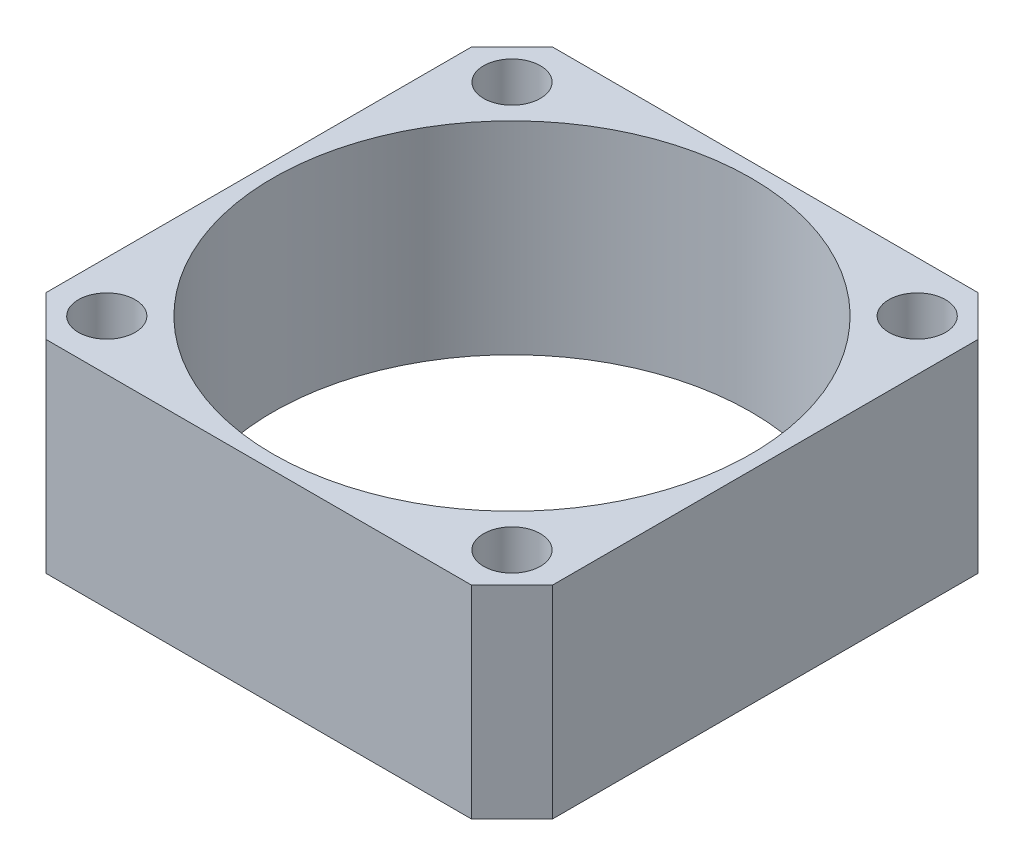
SolidWorks part; units mm, degrees
material "PET"
ref_plane "Front Plane" through (0, 0, 0) normal (0, 0, 1) x (1, 0, 0)
ref_plane "Top Plane" through (0, 0, 0) normal (0, 1, 0) x (1, 0, 0)
ref_plane "Right Plane" through (0, 0, 0) normal (1, 0, 0) x (0, 0, -1)
sketch "Sketch1" plane through (0, 0, 0) normal (0, 1, 0) x (1, 0, 0)
  line L0 (-12.5, 10.5) -> (-10.5, 12.5)
  line L1 (-10.5, -12.5) -> (10.5, -12.5)
  line L2 (-12.5, -10.5) -> (-12.5, 10.5)
  line L3 (-10.5, 12.5) -> (10.5, 12.5)
  line L4 (12.5, -10.5) -> (12.5, 10.5)
  line L5 (-12.5, -12.5) -> (12.5, 12.5) construction
  line L6 (-12.5, 12.5) -> (12.5, -12.5) construction
  line L7 (-10, -10) -> (10, -10)
  line L8 (-10, -10) -> (-10, 10)
  line L9 (-10, 10) -> (10, 10)
  line L10 (10, -10) -> (10, 10)
  line L11 (-10, -10) -> (10, 10) construction
  line L12 (-10, 10) -> (10, -10) construction
  line L13 (10.5, 12.5) -> (12.5, 10.5)
  line L14 (10.5, -12.5) -> (12.5, -10.5)
  line L15 (-12.5, -10.5) -> (-10.5, -12.5)
  circle A0 centre (0, 0) radius 11.8
  circle A1 centre (-10, 10) radius 1.4
  circle A2 centre (10, 10) radius 1.4
  circle A3 centre (10, -10) radius 1.4
  circle A4 centre (-10, -10) radius 1.4
  point P0 (0, 0)
  dimension "D3" = 20
  dimension "D1" = 25
  dimension "D2" = 25
  dimension "D4" = 20
extrude "Boss-Extrude2" add sketch "Sketch1" along normal blind 10 contours L2 L15 L1 L14 L4 L13 L3 L0 A4 L8 A0 A1 L9 A2 L10 A3 L7 | A4 L7 A0 L8 | A3 L10 A0 L7 | A2 L9 A0 L10 | A1 L8 A0 L9
